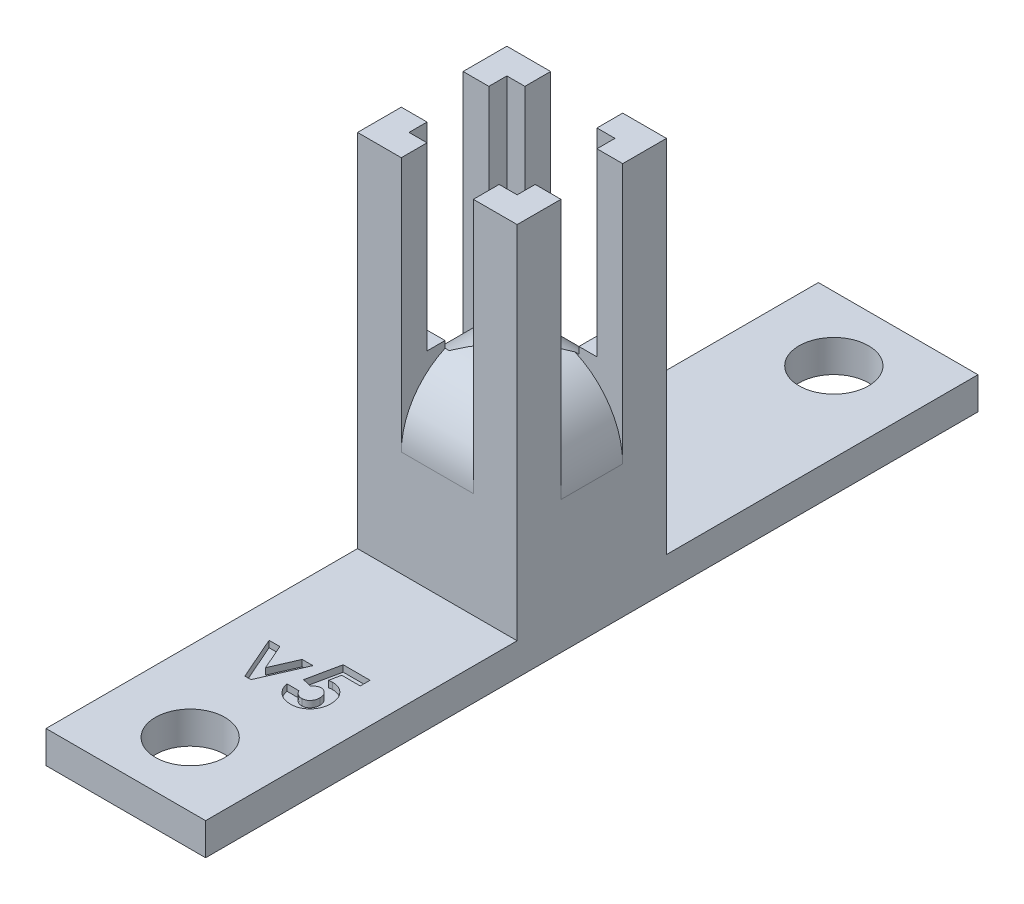
SolidWorks part; units mm, degrees
ref_plane "Front Plane" through (0, 0, 0) normal (0, 0, 1) x (1, 0, 0)
ref_plane "Top Plane" through (0, 0, 0) normal (0, 1, 0) x (1, 0, 0)
ref_plane "Right Plane" through (0, 0, 0) normal (1, 0, 0) x (0, 0, -1)
sketch "Sketch1" plane through (0, 0, 0) normal (0, 1, 0) x (1, 0, 0)
  line L0 (-5.334, 4.826) -> (-5.334, 3.048)
  line L1 (-5.334, -4.826) -> (5.334, -4.826) construction
  line L2 (-5.334, -4.826) -> (-5.334, 4.826) construction
  line L3 (-5.334, 4.826) -> (5.334, 4.826) construction
  line L4 (5.334, -4.826) -> (5.334, 4.826) construction
  line L5 (-5.334, -4.826) -> (5.334, 4.826) construction
  line L6 (-5.334, 4.826) -> (5.334, -4.826) construction
  line L7 (-5.334, 3.048) -> (-7.874, 3.048)
  line L8 (-7.874, 3.048) -> (-7.874, 7.366)
  line L9 (-7.874, 7.366) -> (-3.556, 7.366)
  line L10 (-3.556, 7.366) -> (-3.556, 4.826)
  line L11 (-3.556, 4.826) -> (-5.334, 4.826)
  line L12 (0, 4.826) -> (0, -4.826) construction
  line L13 (-5.334, 0) -> (5.334, 0) construction
  line L14 (7.874, 3.048) -> (7.874, 7.366)
  line L15 (5.334, 3.048) -> (7.874, 3.048)
  line L16 (5.334, 4.826) -> (5.334, 3.048)
  line L17 (3.556, 4.826) -> (5.334, 4.826)
  line L18 (3.556, 7.366) -> (3.556, 4.826)
  line L19 (7.874, 7.366) -> (3.556, 7.366)
  line L20 (5.334, -3.048) -> (7.874, -3.048)
  line L21 (5.334, -4.826) -> (5.334, -3.048)
  line L22 (3.556, -4.826) -> (5.334, -4.826)
  line L23 (3.556, -7.366) -> (3.556, -4.826)
  line L24 (7.874, -7.366) -> (3.556, -7.366)
  line L25 (7.874, -3.048) -> (7.874, -7.366)
  line L26 (-5.334, -3.048) -> (-7.874, -3.048)
  line L27 (-5.334, -4.826) -> (-5.334, -3.048)
  line L28 (-3.556, -4.826) -> (-5.334, -4.826)
  line L29 (-3.556, -7.366) -> (-3.556, -4.826)
  line L30 (-7.874, -7.366) -> (-3.556, -7.366)
  line L31 (-7.874, -3.048) -> (-7.874, -7.366)
  point P0 (0, 0)
  dimension "D1" = 10.668
  dimension "D2" = 9.652
  dimension "D3" = 2.54
  dimension "D4" = 1.778
extrude "Boss-Extrude1" add sketch "Sketch1" along normal blind 17.78
sketch "Sketch2" plane through (0, 0, 0) normal (0, -1, 0) x (-1, 0, 0)
  line L1 (7.874, -7.366) -> (-7.874, -7.366)
  line L2 (7.874, -7.366) -> (7.874, 7.366)
  line L3 (7.874, 7.366) -> (-7.874, 7.366)
  line L4 (-7.874, -7.366) -> (-7.874, 7.366)
extrude "Boss-Extrude2" add sketch "Sketch2" along normal blind 17.78
sketch "Sketch3" plane through (0, -17.78, 0) normal (0, -1, 0) x (-1, 0, 0)
  line L0 (0, 0) -> (7.874, 0) construction
  line L1 (-7.874, -38.1) -> (7.874, -38.1)
  line L2 (-7.874, -38.1) -> (-7.874, 38.1)
  line L3 (-7.874, 38.1) -> (7.874, 38.1)
  line L4 (7.874, -38.1) -> (7.874, 38.1)
  line L5 (-7.874, -38.1) -> (7.874, 38.1) construction
  line L6 (-7.874, 38.1) -> (7.874, -38.1) construction
  line L7 (7.874, -7.366) -> (7.874, 7.366) construction
  circle A0 centre (0, 31.75) radius 3.429
  circle A1 centre (0, -31.75) radius 3.429
  point P0 (0, 0)
  dimension "D2" = 6.858
  dimension "D3" = 31.75
  dimension "D4" = 76.2
extrude "Boss-Extrude3" add sketch "Sketch3" along normal blind 3.175
sketch "Sketch5" plane through (0, -17.78, 0) normal (0, 1, 0) x (1, 0, 0)
  line L0 (-7.874, -23.8163) -> (7.874, -23.8163) construction
  line L1 (-7.874, -38.1) -> (-7.874, -7.366) construction
  line L2 (7.874, -7.366) -> (7.874, -38.1) construction
  text T0 "<b>v5</b>" font "Century Gothic" height in points 22
extrude "Cut-Extrude3" cut sketch "Sketch5" against normal blind 0.635
sketch "Sketch6" plane through (0, 0, 0) normal (1, 0, 0) x (0, 0, -1)
  line L0 (7.366, 17.78) -> (7.366, -17.78) construction
  line L1 (-7.366, -7.366) -> (-7.366, 2.54)
  line L2 (-7.366, 2.54) -> (7.366, 2.54)
  line L3 (7.366, 2.54) -> (7.366, -7.366)
  line L4 (-7.366, -17.78) -> (-7.366, 17.78) construction
  arc A0 (7.366, -7.366) -> (-7.366, -7.366) centre (0, -7.366) ccw
  dimension "D1" = 2.54
extrude "Cut-Extrude4" cut sketch "Sketch6" against normal up to surface and the other way up to surface up to face at (-3.556, 8.89, 6.096) other way up to face at (3.556, 8.89, 6.096)
sketch "Sketch7" plane through (0, 0, 0) normal (0, 0, 1) x (1, 0, 0)
  line L0 (-7.874, -17.78) -> (-7.874, 17.78) construction
  line L1 (-7.874, -7.874) -> (-7.874, 4.5387)
  line L2 (-7.874, 4.5387) -> (7.874, 4.5387)
  line L3 (7.874, -17.78) -> (7.874, 17.78) construction
  line L4 (7.874, 4.5387) -> (7.874, -7.874)
  arc A0 (7.874, -7.874) -> (-7.874, -7.874) centre (0, -7.874) ccw
extrude "Cut-Extrude5" cut sketch "Sketch7" against normal up to surface and the other way up to surface up to face at (-6.604, 8.89, -3.048) other way up to face at (-6.604, 8.89, 3.048)
